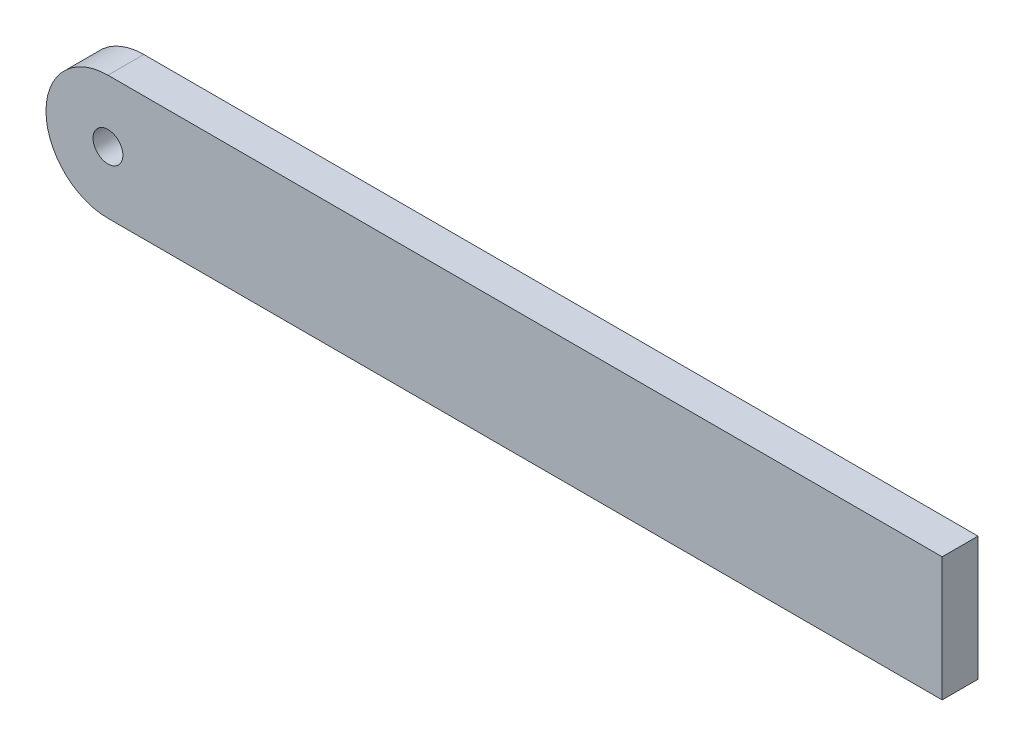
SolidWorks part; units mm, degrees
ref_plane "Front Plane" through (0, 0, 0) normal (0, 0, 1) x (1, 0, 0)
ref_plane "Top Plane" through (0, 0, 0) normal (0, 1, 0) x (1, 0, 0)
ref_plane "Right Plane" through (0, 0, 0) normal (1, 0, 0) x (0, 0, -1)
sketch "Sketch1" plane through (0, 0, 0) normal (0, 0, 1) x (1, 0, 0)
  line L1 (-64.63, 10.375) -> (75, 10.375)
  line L2 (-75, 0.005) -> (-75, -0.005)
  line L3 (-64.63, -10.375) -> (75, -10.375)
  line L4 (75, 10.375) -> (75, -10.375)
  line L5 (-75, 10.375) -> (75, -10.375) construction
  line L6 (-75, -10.375) -> (75, 10.375) construction
  arc A0 (-75, -0.005) -> (-64.63, -10.375) centre (-64.63, -0.005) ccw
  arc A1 (-64.63, 10.375) -> (-75, 0.005) centre (-64.63, 0.005) ccw
  circle A2 centre (-64.63, 0.005) radius 2.5
  point P0 (0, 0)
  dimension "D3" = 10.37
  dimension "D4" = 5
  dimension "D1" = 150
  dimension "D2" = 20.75
extrude "Boss-Extrude1" add sketch "Sketch1" along normal blind 6
